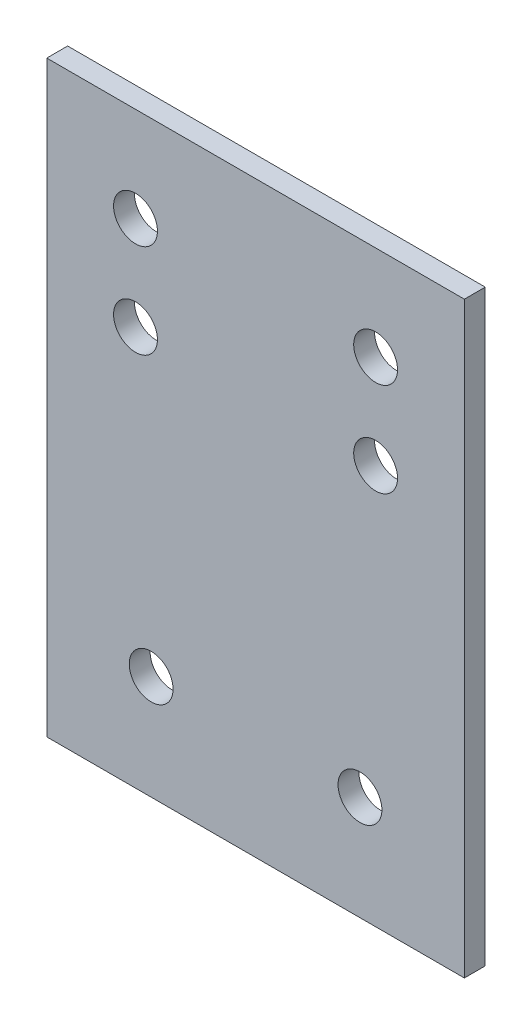
SolidWorks part; units mm, degrees
ref_plane "Front Plane" through (0, 0, 0) normal (0, 0, 1) x (1, 0, 0)
ref_plane "Top Plane" through (0, 0, 0) normal (0, 1, 0) x (1, 0, 0)
ref_plane "Right Plane" through (0, 0, 0) normal (1, 0, 0) x (0, 0, -1)
sketch "Sketch1" plane through (0, 0, 0) normal (0, 0, 1) x (1, 0, 0)
  line L1 (-1740.4212, -1861.9194) -> (-1820.4212, -1861.9194)
  line L2 (-1740.4212, -1861.9194) -> (-1740.4212, -1749.2958)
  line L3 (-1740.4212, -1749.2958) -> (-1820.4212, -1749.2958)
  line L4 (-1820.4212, -1861.9194) -> (-1820.4212, -1749.2958)
extrude "Boss-Extrude1" add sketch "Sketch1" along normal blind 4
hole_wizard "M8 Clearance Hole1" positions "Sketch3" profile "Sketch2" hole size "M8" standard "ISO" end condition through all
sketch "Sketch3" plane through (0, 0, 4) normal (0, 0, 1) x (1, 0, 0)
  point P0 (-1760.4212, -1841.9194)
  point P2 (-1803.4212, -1767.4194)
  point P4 (-1803.4212, -1767.4194)
  point P6 (-1800.4212, -1841.9194)
  point P8 (-1757.4212, -1785.4194)
  point P10 (-1757.4212, -1767.4194)
  point P28 (-1803.4212, -1785.4194)
sketch "Sketch2" plane through (-1760.4212, -1841.9194, 4) normal (1, 0, 0) x (0, -1, 0)
  line L0 (0, 0) -> (0, 4)
  line L1 (0, 4) -> (4.2, 4)
  line L2 (4.2, 4) -> (4.2, 0)
  line L5 (4.2, 0) -> (0, 0)
  line L11 (0, -6.35) -> (0, 107.95) construction
  dimension "Thru Hole Dia." = 8.4
  dimension "Thru Hole Depth" = 4
